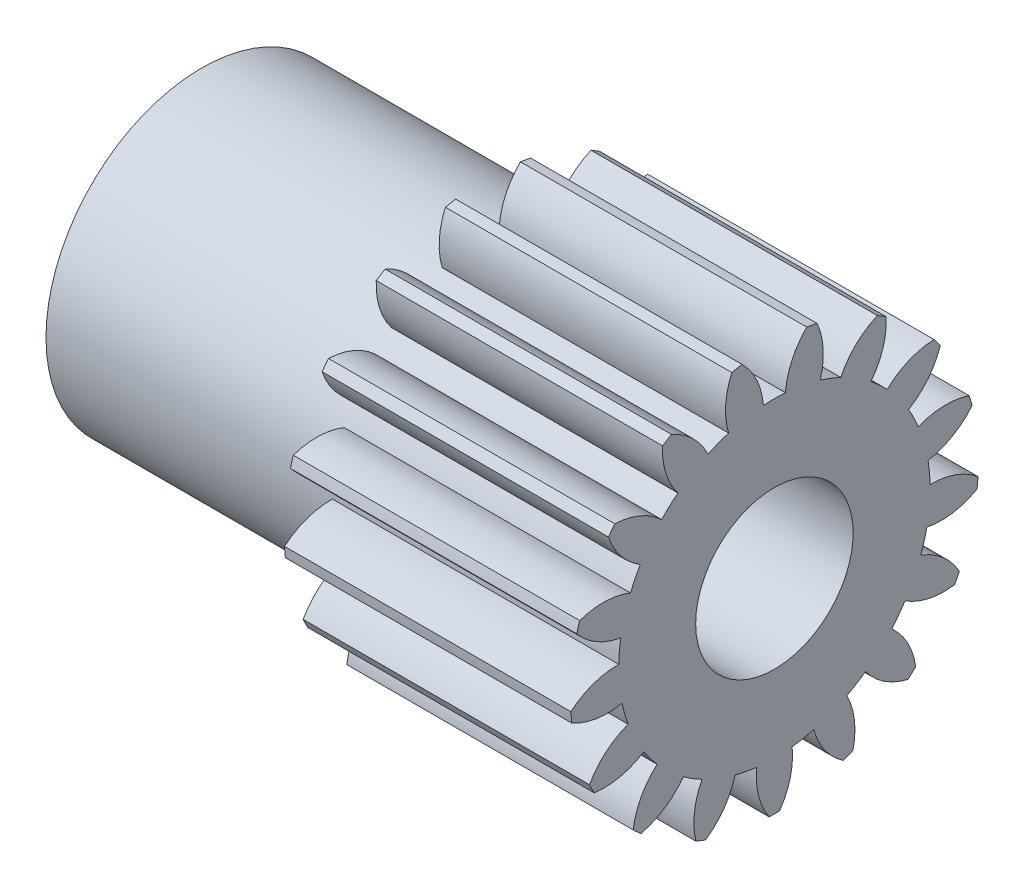
SolidWorks part; units mm, degrees
ref_plane "Plane1" through (0, 0, 0) normal (0, 0, 1) x (1, 0, 0)
ref_plane "Plane2" through (0, 0, 0) normal (0, 1, 0) x (1, 0, 0)
ref_plane "Plane3" through (0, 0, 0) normal (1, 0, 0) x (0, 0, -1)
other "Configuration Table"
sketch "HoldingSke" plane through (0, 0, 0) normal (0, 1, 0) x (1, 0, 0)
  line L0 (0, 0) -> (0.6375, -0.1949)
  line L1 (-15, 0) -> (100, 0) construction
  line L2 (0, 0) -> (-2.1039, 2.3779)
  line L3 (0, 0) -> (-11.863, 4.5341)
  line L4 (0, 0) -> (8.2586, 2.5249)
  line L5 (0, 0) -> (-37.4781, -13.9782)
  line L6 (0, 0) -> (-16.5793, -11.1861)
  line L7 (-2.1039, 2.3779) -> (6.5061, 41.4403)
  line L8 (-76.2, 54.61) -> (-74.4, 54.61)
  line L9 (-71.009, 38.7566) -> (-53.1078, 45.2721)
  line L10 (-76.2, 71.12) -> (104.1128, 71.12)
  line L11 (0, 0) -> (-20, 0)
  line L12 (-76.2, 101.6) -> (-76.147, 101.6)
  line L13 (24.9733, 27.94) -> (52.9518, 28.4284)
  line L14 (24.9733, 27.94) -> (24.9743, 27.94)
  line L15 (24.9733, 27.94) -> (100.4006, 29.5858)
  line L16 (-63.627, -1.5) -> (-12.827, -1.5)
  circle A0 centre (0, 0) radius 5.5
  circle A1 centre (0, 0) radius 10.874
  circle A2 centre (0, 0) radius 37.5
  circle A3 centre (0, 0) radius 5.5
  dimension "MHD" = 21.748
  dimension "Hub_dia" = 75
  dimension "Bore" = 11
  dimension "MBD" = 11
  dimension "Num_teeth" = 17
  dimension "Pitch" = 0.6667
  dimension "Overall_len" = 40
  dimension "Show_teeth" = 17
  dimension "Thickness" = 20
  dimension "OAL" = 40.0001
  dimension "T_dim" = 1.8
  dimension "Ap" = 20
  dimension "H" = 19.05
  dimension "Pitch_radius" = 180.3128
  dimension "Width" = 20
  dimension "Backlash" = 0.053
  dimension "Addendum_fac" = 1
  dimension "Dedendum_fac" = 1.25
  dimension "Clearance_fac" = 0.25
  dimension "Dedendum_add" = 0.001
  dimension "Module" = 1.5
sketch "BasProSke" plane through (0, 0, 0) normal (0, 1, 0) x (1, 0, 0)
  line L0 (-10, 0) -> (60, 0) construction
  line L1 (0, 0) -> (0, 14.25)
  line L2 (0, 0) -> (20, 0)
  line L3 (20, 0) -> (20, 14.25)
  line L4 (20, 14.25) -> (0, 14.25)
  dimension "Thickness" = 20
  dimension "Diameter" = 28.5
revolve "Base-Revolve" add sketch "BasProSke" angle 360 about L0
sketch "TooCutSke" plane through (0, 0, 0) normal (1, 0, 0) x (0, 0, -1)
  line L1 (0, 0) -> (0, 107) construction
  line L2 (0, 0) -> (-1.2691, 12.6867) construction
  line L3 (0, 0) -> (-4.6687, 24.9751) construction
  line L4 (-1.2691, 12.6867) -> (-2.3343, 12.4876) construction
  arc A0 (0.7694, 10.8467) -> (-0.7694, 10.8467) centre (0, 0) ccw
  arc A1 (2.2806, 14.0921) -> (-2.2806, 14.0921) centre (0, 0) ccw
  circle A2 centre (0, 0) radius 12.75 construction
  circle A3 centre (0, 0) radius 11.9811 construction
  arc A4 (-0.7694, 10.8467) -> (-2.2806, 14.0921) centre (-5.8542, 10.4535) ccw
  arc A5 (2.2806, 14.0921) -> (0.7694, 10.8467) centre (5.8542, 10.4535) ccw
  dimension "Root_dia" = 21.748
  dimension "Overcut_dia" = 28.5508
  dimension "Pitch_dia" = 25.5
  dimension "Base_dia" = 23.9622
  dimension "Flank_rad" = 5.1
  dimension "Half_ang" = 10.588
  dimension "Half_CT" = 1.0837
extrude "ToothCut" cut sketch "TooCutSke" along normal through all
fillet "Breaks" [suppressed] radius 0.03
fillet "RootFillets" [suppressed] radius 0.376
pattern_circular "TeethCuts" count 17 every 21.176 about axis through (-10, 0, 0) along (1, 0, 0) of "ToothCut", "RootFillets", "Breaks"
sketch "HubNeaOneSke" plane through (0, 0, 0) normal (-1, 0, 0) x (0, 0, 1)
  circle A0 centre (0, 0) radius 10.874
  dimension "Diameter" = 21.748
extrude "HubNearOne" add sketch "HubNeaOneSke" along normal blind 20.0001
sketch "HubNeaBotSke" plane through (0, 0, 0) normal (-1, 0, 0) x (0, 0, 1)
  circle A0 centre (0, 0) radius 10.874
  dimension "Diameter" = 21.748
extrude "HubNearBoth" [suppressed] add sketch "HubNeaBotSke" along normal blind 10
ref_plane "FarPln" through (20, 0, 0) normal (1, 0, 0) x (0, 0, -1)
sketch "HubFarSke" plane through (20, 0, 0) normal (1, 0, 0) x (0, 0, -1)
  circle A0 centre (0, 0) radius 10.874
  dimension "Diameter" = 21.748
extrude "HubFar" [suppressed] add sketch "HubFarSke" along normal blind 10
sketch "BorSke" plane through (0, 0, 0) normal (1, 0, 0) x (0, 0, -1)
  circle A0 centre (0, 0) radius 5.5
  dimension "Diameter" = 11
extrude "Bore" cut sketch "BorSke" along normal mid plane 80.0001
sketch "KeySke" plane through (0, 0, 0) normal (1, 0, 0) x (0, 0, -1)
  line L0 (-2, 0) -> (-2, 7.3)
  line L1 (-2, 7.3) -> (2, 7.3)
  line L2 (2, 7.3) -> (2, 0)
  line L3 (0, 0) -> (0, 34) construction
  line L4 (-2, 0) -> (2, 0)
  dimension "Offset" = 7.3
  dimension "Width" = 4
extrude "Keyway" [suppressed] cut sketch "KeySke" along normal mid plane 80.0001
pattern_circular "Keyway2" [suppressed] count 2 every 90 about axis through (-10, 0, 0) along (1, 0, 0)
equation "' \"Module@HoldingSke\" = 6.35"
equation "' \"Num_teeth@HoldingSke\" = 12"
equation "' \"Ap@HoldingSke\" =  20"
equation "' \"Ap@HoldingSke\" = 20"
equation "' \"Width@HoldingSke\" = 0.5 * 25.4"
equation "' \"Hub_dia@HoldingSke\"= 1 * 25.4"
equation "' \"Hub_dia@HoldingSke\" = 1 * 25.4"
equation "' \"Overall_len@HoldingSke\" = 1.0 * 25.4"
equation "' \"Bore@HoldingSke\" = 0.75 * 25.4"
equation "' \"T_dim@HoldingSke\" = 0.1 * 25.4"
equation "' \"Width@KeySke\" = 0.25 * 25.4"
equation "' \"Show_teeth@HoldingSke\" = 13"
equation "' \"Backlash@HoldingSke\" = 0.009 * 25.4"
equation "' \"Addendum_fac@HoldingSke\" = 1.0"
equation "' \"Dedendum_fac@HoldingSke\" = 1.25"
equation "' \"Dedendum_add@HoldingSke\" = 0.00005 * 25.4"
equation "' \"Clearance_fac@HoldingSke\" = 0.25"
equation "\"Pitch@HoldingSke\" = 1 / \"Module@HoldingSke\""
equation "\"Overcut_dia@TooCutSke\" = (\"Num_teeth@HoldingSke\" + 2 * \"Addendum_fac@HoldingSke\") / \"Pitch@HoldingSke\" + 0.002 * 25.4"
equation "\"Pitch_dia@TooCutSke\" = \"Num_teeth@HoldingSke\" / \"Pitch@HoldingSke\""
equation "\"Base_dia@TooCutSke\" = \"Num_teeth@HoldingSke\" / \"Pitch@HoldingSke\" * cos((\"Ap@HoldingSke\"  * 3.14159265 / 180))"
equation "\"Root_dia@TooCutSke\" = (\"Num_teeth@HoldingSke\" + 2) / \"Pitch@HoldingSke\" - 2 * (\"Addendum_fac@HoldingSke\" + \"Dedendum_fac@HoldingSke\") / \"Pitch@HoldingSke\" - \"Dedendum_add@HoldingSke\" * 2"
equation "\"Half_ang@TooCutSke\" = 180 / \"Num_teeth@HoldingSke\""
equation "\"Half_CT@TooCutSke\" = \"Num_teeth@HoldingSke\" / \"Pitch@HoldingSke\" * sin((3.14159265 / 2 / \"Num_teeth@HoldingSke\")) / 2 - 7 * \"Backlash@HoldingSke\" / 4"
equation "\"Flank_rad@TooCutSke\" = \"Num_teeth@HoldingSke\" / \"Pitch@HoldingSke\" / 5"
equation "\"Radius@RootFillets\" = \"Clearance_fac@HoldingSke\" / \"Pitch@HoldingSke\" + \"Dedendum_add@HoldingSke\""
equation "\"Break_rad@Breaks\" = 0.02 / \"Pitch@HoldingSke\""
equation "\"Thickness@HoldingSke\" = \"Width@HoldingSke\""
equation "\"OAL@HoldingSke\" = \"Thickness@HoldingSke\""
equation "\"MHD@HoldingSke\" = (\"Num_teeth@HoldingSke\" + 2) / \"Pitch@HoldingSke\" - 2 * (\"Addendum_fac@HoldingSke\" + \"Dedendum_fac@HoldingSke\")  / \"Pitch@HoldingSke\" - \"Dedendum_add@HoldingSke\" * 2"
equation "\"MBD@HoldingSke\" = (\"Num_teeth@HoldingSke\" + 2) / \"Pitch@HoldingSke\" - 2 * (\"Addendum_fac@HoldingSke\" + \"Dedendum_fac@HoldingSke\")  / \"Pitch@HoldingSke\" - \"Dedendum_add@HoldingSke\" * 2 - 0.002 * 25.4"
equation "\"MHD@HoldingSke\" = ((sgn( \"MHD@HoldingSke\" - \"Hub_dia@HoldingSke\" )-1)*( \"MHD@HoldingSke\" - \"Hub_dia@HoldingSke\" ))/-2+ \"Hub_dia@HoldingSke\""
equation "\"MBD@HoldingSke\" = ((sgn( \"MBD@HoldingSke\" - \"Bore@HoldingSke\" )-1)*( \"MBD@HoldingSke\" - \"Bore@HoldingSke\" ))/-2+ \"Bore@HoldingSke\""
equation "\"OAL@HoldingSke\" = ((sgn( \"OAL@HoldingSke\" - \"Overall_len@HoldingSke\" )+1)*( \"OAL@HoldingSke\" - \"Overall_len@HoldingSke\" ))/2 + \"Overall_len@HoldingSke\" + 0.000002 * 25.4"
equation "\"Num_teeth@TeethCuts\" = int( \"Show_teeth@HoldingSke\" ) + 1"
equation "\"Num_teeth@TeethCuts\" = ((sgn( \"Num_teeth@TeethCuts\" - \"Num_teeth@HoldingSke\" )-1)*( \"Num_teeth@TeethCuts\" - \"Num_teeth@HoldingSke\" ))/-2+ \"Num_teeth@HoldingSke\""
equation "\"Num_teeth@TeethCuts\" = ((sgn( \"Num_teeth@TeethCuts\" - 2.0)+1)*( \"Num_teeth@TeethCuts\" - 2.0))/2 +2.0"
equation "\"Angle@TeethCuts\" = 360.0 / \"Num_teeth@HoldingSke\""
equation "\"Diameter@BasProSke\" = (\"Num_teeth@HoldingSke\" + 2 * \"Addendum_fac@HoldingSke\") / \"Pitch@HoldingSke\""
equation "\"Thickness@BasProSke\"  = \"Thickness@HoldingSke\""
equation "' \"Fillet_rad@BasProSke\" =  \"Thickness@HoldingSke\" * 0.05"
equation "' \"Fillet_rad@BasProSke\" = \"Thickness@HoldingSke\" * 0.05"
equation "\"MHD@HoldingSke\" = ((sgn( \"MHD@HoldingSke\" - \"Root_dia@TooCutSke\" )-1)*( \"MHD@HoldingSke\" - \"Root_dia@TooCutSke\" ))/-2+ \"Root_dia@TooCutSke\""
equation "\"Diameter@HubNeaOneSke\" = \"MHD@HoldingSke\""
equation "\"Length@HubNearOne\" = \"OAL@HoldingSke\" - \"Thickness@BasProSke\""
equation "\"Diameter@HubNeaBotSke\" = \"MHD@HoldingSke\""
equation "\"Length@HubNearBoth\" = ( \"OAL@HoldingSke\" - \"Thickness@BasProSke\" ) / 2.0"
equation "\"Thickness@FarPln\" = \"Thickness@BasProSke\""
equation "\"Diameter@HubFarSke\" = \"MHD@HoldingSke\""
equation "\"Length@HubFar\" = ( \"OAL@HoldingSke\" - \"Thickness@BasProSke\" ) / 2.0"
equation "\"Diameter@BorSke\" = \"MBD@HoldingSke\""
equation "\"D1@Bore\" = \"OAL@HoldingSke\" * 2.0"
equation "\"D1@Keyway\" = \"OAL@HoldingSke\" * 2.0"
equation "\"Offset@KeySke\" = \"T_dim@HoldingSke\" + \"MBD@HoldingSke\" / 2.0"
